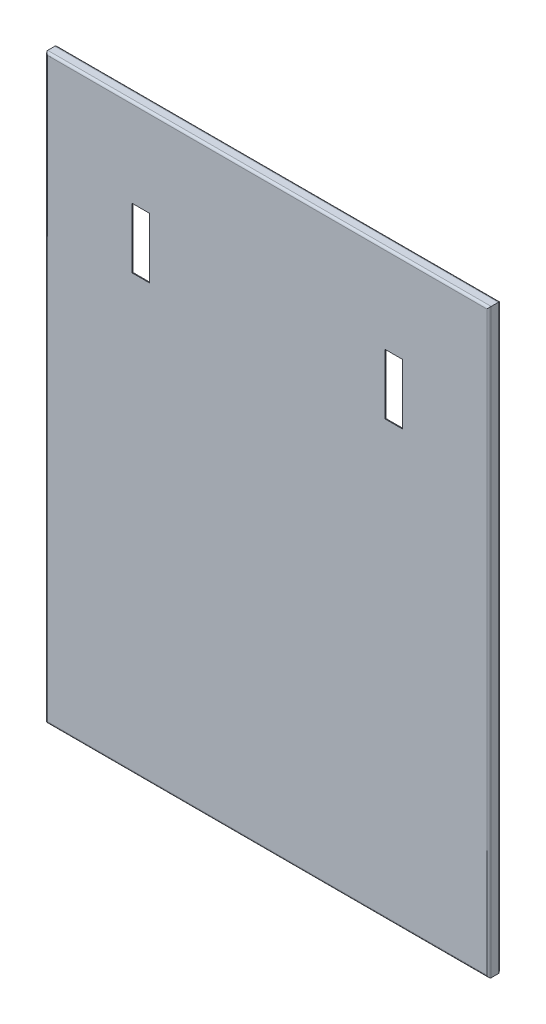
SolidWorks part; units mm, degrees
ref_plane "정면" through (0, 0, 0) normal (0, 0, 1) x (1, 0, 0)
ref_plane "윗면" through (0, 0, 0) normal (0, 1, 0) x (1, 0, 0)
ref_plane "우측면" through (0, 0, 0) normal (1, 0, 0) x (0, 0, -1)
sketch "스케치1" plane through (0, 0, 0) normal (0, 0, 1) x (1, 0, 0)
  line L1 (0, 0) -> (640, 0)
  line L2 (0, 0) -> (0, 839)
  line L3 (0, 839) -> (640, 839)
  line L4 (640, 0) -> (640, 839)
  line L5 (125, 712) -> (150, 712)
  line L6 (125, 712) -> (125, 625)
  line L7 (125, 625) -> (150, 625)
  line L8 (150, 712) -> (150, 625)
  line L9 (490, 712) -> (515, 712)
  line L10 (490, 712) -> (490, 625)
  line L11 (490, 625) -> (515, 625)
  line L12 (515, 712) -> (515, 625)
  point P14 (150, 668.5)
  dimension "D1" = 839
  dimension "D2" = 640
  dimension "D3" = 125
  dimension "D4" = 25
  dimension "D5" = 340
  dimension "D6" = 25
  dimension "D7" = 87
  dimension "D8" = 625
extrude "보스-돌출1" add sketch "스케치1" along normal blind 1.2
sketch "스케치2" plane through (0, 0, 0) normal (0, 0, -1) x (-1, 0, 0)
  line L0 (-1.2, 837.8) -> (-638.8, 837.8)
  line L1 (-638.8, 837.8) -> (-638.8, 1.2)
  line L2 (-638.8, 1.2) -> (-1.2, 1.2)
  line L3 (-1.2, 1.2) -> (-1.2, 837.8)
  line L4 (0, 0) -> (0, 839)
  line L5 (0, 839) -> (-640, 839)
  line L6 (-640, 839) -> (-640, 0)
  line L7 (-640, 0) -> (0, 0)
  line L8 (0, 0) -> (0, 839)
  line L9 (0, 839) -> (-640, 839)
  line L10 (-640, 839) -> (-640, 0)
  line L11 (-640, 0) -> (0, 0)
  dimension "D1" = 0
  dimension "D2" = 1.2
extrude "보스-돌출2" add sketch "스케치2" along normal blind 15.5
sketch "스케치3" plane through (0, 0, -15.5) normal (0, 0, -1) x (-1, 0, 0)
  line L0 (-15, 824) -> (-625, 824)
  line L1 (-625, 824) -> (-625, 15)
  line L2 (-625, 15) -> (-15, 15)
  line L3 (-15, 15) -> (-15, 824)
  line L4 (-640, 0) -> (0, 0)
  line L5 (0, 0) -> (0, 839)
  line L6 (0, 839) -> (-640, 839)
  line L7 (-640, 839) -> (-640, 0)
  line L8 (-640, 0) -> (0, 0)
  line L9 (0, 0) -> (0, 839)
  line L10 (0, 839) -> (-640, 839)
  line L11 (-640, 839) -> (-640, 0)
  dimension "D1" = 0
  dimension "D2" = 15
extrude "보스-돌출3" add sketch "스케치3" against normal blind 1.2
fillet "필렛1" radius 2 12 edges at (638.8, 419.5, 0) (638.8, 419.5, -14.3) (320, 1.2, 0) (320, 1.2, -14.3) (638.8, 1.2, -7.15) (1.2, 419.5, 0) (1.2, 419.5, -14.3) (1.2, 1.2, -7.15) (320, 837.8, 0) (638.8, 837.8, -7.15) (320, 837.8, -14.3) (1.2, 837.8, -7.15)
fillet "필렛2" radius 3.2 4 edges at (320, 839, 1.2) (320, 0, 1.2) (0, 419.5, 1.2) (640, 419.5, 1.2)
fillet "필렛3" radius 3.2 4 edges at (640, 419.5, -15.5) (320, 839, -15.5) (0, 419.5, -15.5) (320, 0, -15.5)
